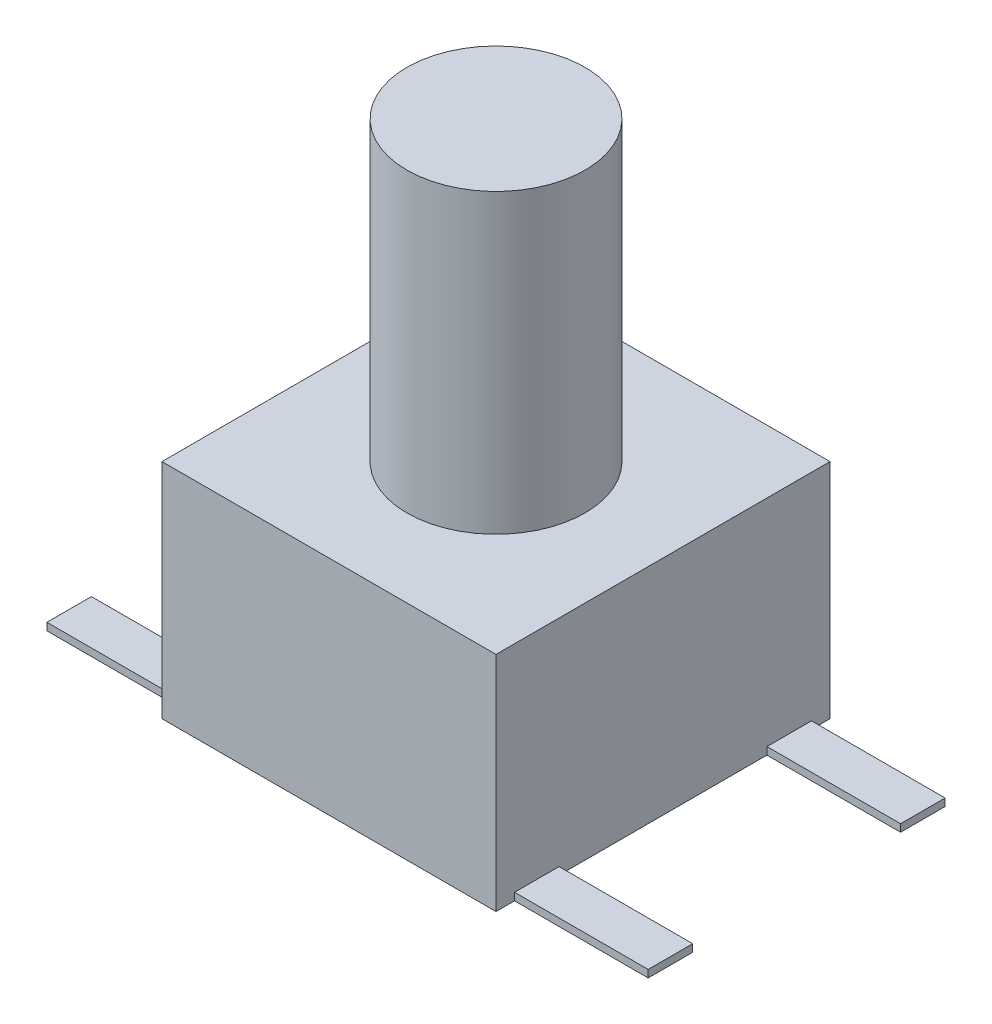
SolidWorks part; units mm, degrees
ref_plane "Спереди" through (0, 0, 0) normal (0, 0, 1) x (1, 0, 0)
ref_plane "Сверху" through (0, 0, 0) normal (0, 1, 0) x (1, 0, 0)
ref_plane "Справа" through (0, 0, 0) normal (1, 0, 0) x (0, 0, -1)
sketch "Эскиз1" plane through (0, 0, 0) normal (0, 1, 0) x (1, 0, 0)
  line L0 (0, 2.25) -> (0, -2.25) construction
  line L1 (-2.25, 2.25) -> (2.25, 2.25)
  line L2 (-2.25, 2.25) -> (-2.25, -2.25)
  line L3 (-2.25, -2.25) -> (2.25, -2.25)
  line L4 (2.25, 2.25) -> (2.25, -2.25)
  point P7 (0, 0)
  dimension "D1" = 4.5
extrude "Бобышка-Вытянуть1" add sketch "Эскиз1" along normal blind 3
sketch "Эскиз2" plane through (0, 0, 0) normal (0, 1, 0) x (1, 0, 0)
  circle A0 centre (0, 0) radius 1.2
  dimension "D1" = 2.4
extrude "Бобышка-Вытянуть2" add sketch "Эскиз2" along normal blind 7
sketch "Эскиз3" plane through (0, 0, 0) normal (0, 1, 0) x (1, 0, 0)
  line L0 (-2.25, 2.25) -> (-2.25, -2.25) construction
  line L1 (-2.25, -2) -> (-4.05, -2)
  line L2 (-2.25, -2) -> (-2.25, -1.4)
  line L3 (-2.25, -1.4) -> (-4.05, -1.4)
  line L4 (-4.05, -2) -> (-4.05, -1.4)
  line L5 (-50, 0) -> (50, 0) construction
  line L6 (-4.05, 2) -> (-4.05, 1.4)
  line L7 (-2.25, 1.4) -> (-4.05, 1.4)
  line L8 (-2.25, 2) -> (-2.25, 1.4)
  line L9 (-2.25, 2) -> (-4.05, 2)
  line L10 (0, -50) -> (0, 50) construction
  line L11 (2.25, 2) -> (4.05, 2)
  line L12 (2.25, 2) -> (2.25, 1.4)
  line L13 (2.25, 1.4) -> (4.05, 1.4)
  line L14 (4.05, 2) -> (4.05, 1.4)
  line L15 (4.05, -2) -> (4.05, -1.4)
  line L16 (2.25, -1.4) -> (4.05, -1.4)
  line L17 (2.25, -2) -> (2.25, -1.4)
  line L18 (2.25, -2) -> (4.05, -2)
  dimension "D1" = 0.6
  dimension "D2" = 4
  dimension "D3" = 1.8
extrude "Бобышка-Вытянуть3" add sketch "Эскиз3" along normal blind 0.1 separate body
